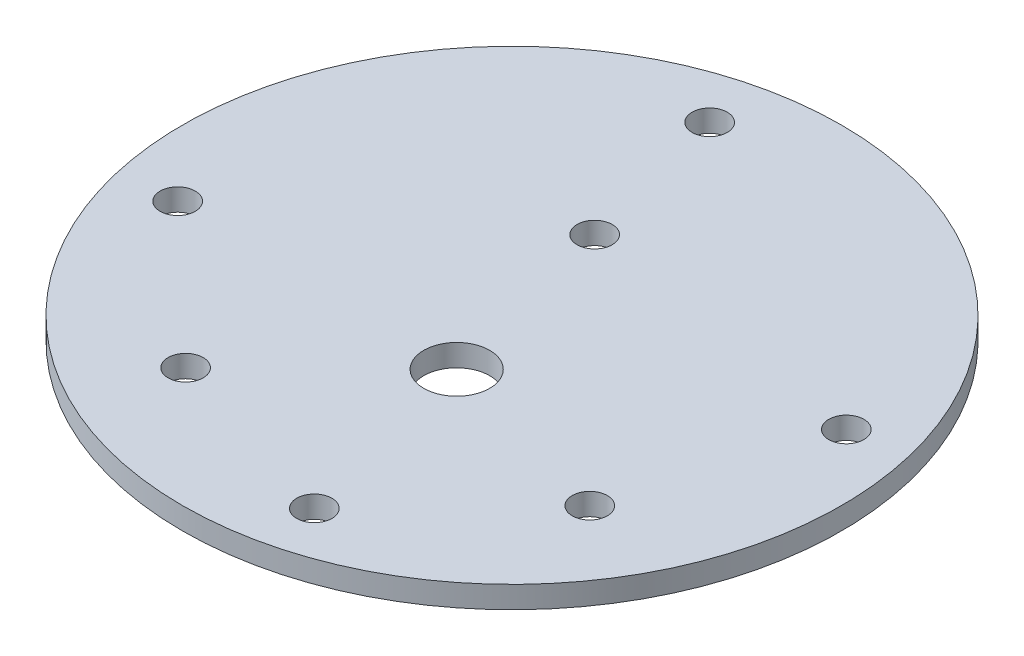
SolidWorks part; units mm, degrees
ref_plane "前视基准面" through (0, 0, 0) normal (0, 0, 1) x (1, 0, 0)
ref_plane "上视基准面" through (0, 0, 0) normal (0, 1, 0) x (1, 0, 0)
ref_plane "右视基准面" through (0, 0, 0) normal (1, 0, 0) x (0, 0, -1)
sketch "草图1" plane through (0, 0, 0) normal (0, 1, 0) x (1, 0, 0)
  circle A0 centre (0, 0) radius 3
  circle A2 centre (-12.466, -12.2107) radius 1.6
  circle A3 centre (-4.3417, 16.9012) radius 1.6
  circle A4 centre (16.8078, -4.6906) radius 1.6
  circle A5 centre (-1.7408, 6.7765) radius 30
  circle A7 centre (-7.9603, 30.9906) radius 1.6 construction
  circle A8 centre (-7.9603, 30.9906) radius 1.6
  circle A9 centre (4.4786, -17.4375) radius 1.6 construction
  circle A10 centre (22.4732, 12.996) radius 1.6 construction
  circle A11 centre (-25.9548, 0.5571) radius 1.6 construction
  circle A12 centre (4.4786, -17.4375) radius 1.6
  circle A13 centre (22.4732, 12.996) radius 1.6
  circle A14 centre (-25.9548, 0.5571) radius 1.6
  point P0 (0, 0)
  point P11 (0.0002, -36.9966)
  point P15 (0, 0)
  point P17 (0, -26.3665)
  point P18 (14.5672, 8.4104)
  point P19 (-12.5295, 7.2339)
  point P20 (0, 0)
  point P21 (0, 0)
  point P22 (0, 0)
  point P23 (0, 0)
  point P24 (23.7118, 7.4368)
  point P25 (-9.8933, -14.3745)
  dimension "D1" = 6
  dimension "D2" = 3.2
  dimension "D3" = 3
extrude "凸台-拉伸1" add sketch "草图1" along normal blind 2
